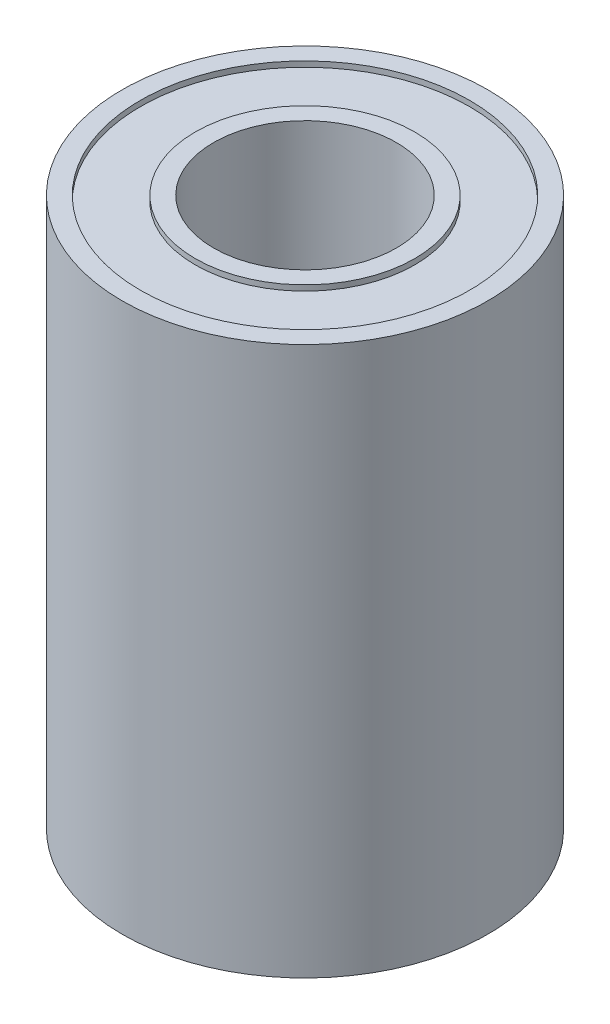
SolidWorks part; units mm, degrees
ref_plane "Спереди" through (0, 0, 0) normal (0, 0, 1) x (1, 0, 0)
ref_plane "Сверху" through (0, 0, 0) normal (0, 1, 0) x (1, 0, 0)
ref_plane "Справа" through (0, 0, 0) normal (1, 0, 0) x (0, 0, -1)
sketch "Эскиз1" plane through (0, 0, 0) normal (0, 1, 0) x (1, 0, 0)
  circle A0 centre (0, 0) radius 5
  circle A1 centre (0, 0) radius 2.5
  dimension "D1" = 10
  dimension "D2" = 5
extrude "Бобышка-Вытянуть1" add sketch "Эскиз1" along normal blind 7.5
sketch "Эскиз2" plane through (0, 7.5, 0) normal (0, 1, 0) x (1, 0, 0)
  circle A0 centre (0, 0) radius 3
  circle A1 centre (0, 0) radius 4.5
  circle A2 centre (0, 0) radius 2.5 construction
  circle A3 centre (0, 0) radius 5 construction
  dimension "D1" = 0.5
  dimension "D2" = 0.5
extrude "Вырез-Вытянуть1" cut sketch "Эскиз2" against normal blind 0.15
mirror "Зеркальное отражение1" about plane through (0, 0, 0) normal (0, 1, 0) of bodies 104
equation "\"motor_diameter\"= 30"
equation "\"mm_diameter\"= IIF ( \"motor_diameter\" < 34 , 41 , \"motor_diameter\" + 8 )"
equation "\"upper_shafts_diameter\"= 5"
equation "\"upper_shats_length\" = 180"
equation "\"upper_bearing_d1\"= 10"
equation "\"upper_bearing_d2\"= 5"
equation "\"upper_bearing_h\"= 15"
equation "\"lower_shafts_diameter\"= 5"
equation "\"lower_shafts_length\"= 230"
equation "\"lower_bearing_d1\" = 10"
equation "\"lower_bearing_d2\"= 5"
equation "\"lower_bearing_h\"= 15"
equation "\"print_offset\"= 0.2"
equation "\"bh_screws_d\"= 2"
equation "\"bh_screws_h\"= 20"
equation "\"bh_screws_hh_d\"= 3.4"
equation "\"bh_screws_hh_h\"= 2"
equation "\"bh_nut_d\"= 3.8"
equation "\"bh_nut_h\"= 2"
equation "\"motor_screws_d\"= 3"
equation "\"motor_screws_h\"= 16"
equation "\"motor_screws_hh_d\"= 5.5"
equation "\"motor_screws_hh_h\"= 3"
equation "\"plate_hole_distance\"= 25.4"
equation "\"plate_screws_d\"= 6.5"
equation "\"D1@Бобышка-Вытянуть1\"=\"upper_bearing_h\"/2"
equation "\"D1@Эскиз2\"=(\"upper_bearing_d1\"-\"upper_bearing_d2\")*0.1"
equation "\"D2@Эскиз2\"=\"D1@Эскиз2\""
equation "\"D1@Вырез-Вытянуть1\"=\"upper_bearing_h\"*0.01"
